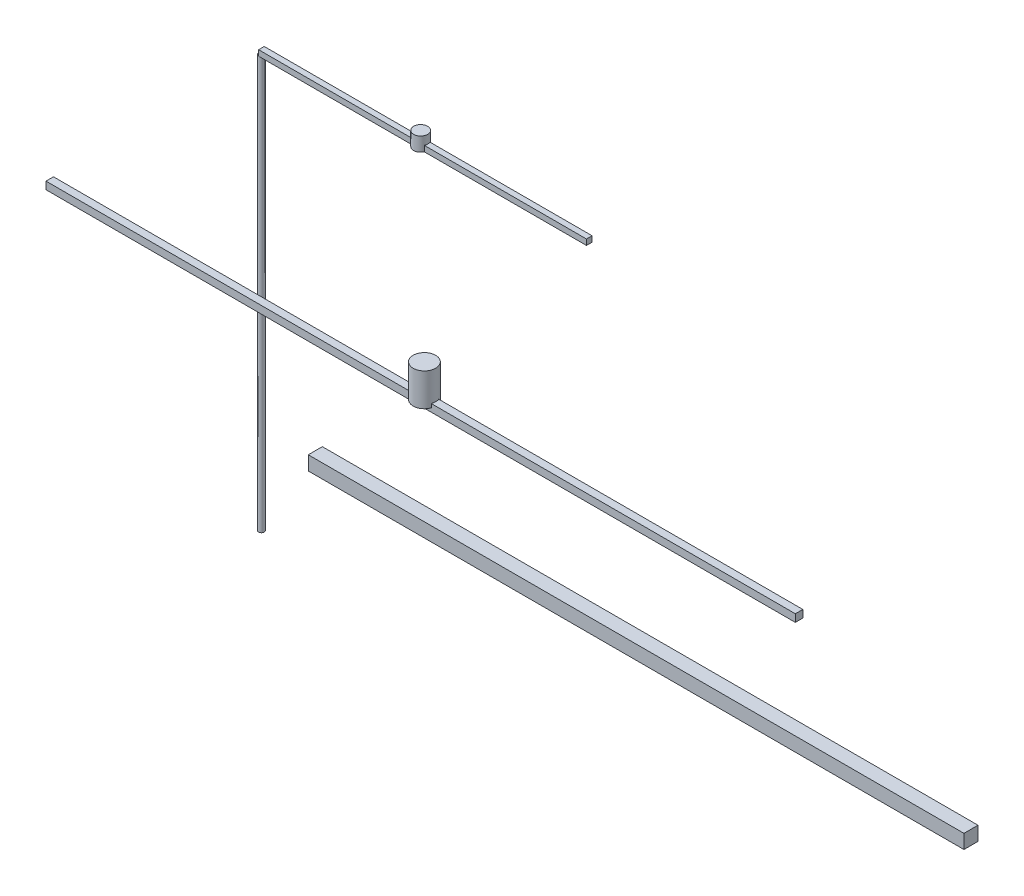
SolidWorks part; units mm, degrees
ref_plane "Front Plane" through (0, 0, 0) normal (0, 0, 1) x (1, 0, 0)
ref_plane "Top Plane" through (0, 0, 0) normal (0, 1, 0) x (1, 0, 0)
ref_plane "Right Plane" through (0, 0, 0) normal (1, 0, 0) x (0, 0, -1)
other "Configuration Table"
sketch "Sketch1" plane through (0, 0, 0) normal (0, 1, 0) x (1, 0, 0)
  circle A0 centre (-3500, 0) radius 30
extrude "Boss-Extrude1" add sketch "Sketch1" along normal blind 4400
sketch "Sketch2" plane through (0, 0, 0) normal (0, 1, 0) x (1, 0, 0)
  line L1 (-3500, -30) -> (0, -30)
  line L2 (-3500, -30) -> (-3500, 30)
  line L3 (-3500, 30) -> (0, 30)
  line L4 (0, -30) -> (0, 30)
  circle A0 centre (-3500, 0) radius 30 construction
extrude "Boss-Extrude2" add sketch "Sketch2" along normal blind 60 from offset 4400
sketch "Sketch3" plane through (0, 0, 0) normal (0, 1, 0) x (1, 0, 0)
  circle A0 centre (-1800, 0) radius 75
extrude "Boss-Extrude3" add sketch "Sketch3" along normal blind 150 from offset 4400
sketch "Sketch4" plane through (0, 0, 0) normal (0, 1, 0) x (1, 0, 0)
  line L1 (-4000, -1800) -> (4000, -1800)
  line L2 (-4000, -1800) -> (-4000, -1720)
  line L3 (-4000, -1720) -> (4000, -1720)
  line L4 (4000, -1800) -> (4000, -1720)
extrude "Boss-Extrude4" add sketch "Sketch4" along normal blind 80 from offset 3800
sketch "Sketch5" plane through (0, 0, 0) normal (0, 1, 0) x (1, 0, 0)
  circle A0 centre (0, -1760) radius 120
extrude "Boss-Extrude5" add sketch "Sketch5" along normal blind 350 from offset 3840
sketch "Sketch6" plane through (0, 0, 0) normal (0, 1, 0) x (1, 0, 0)
  line L1 (-3500, 500) -> (3500, 500)
  line L2 (-3500, 500) -> (-3500, 650)
  line L3 (-3500, 650) -> (3500, 650)
  line L4 (3500, 500) -> (3500, 650)
extrude "Boss-Extrude6" add sketch "Sketch6" along normal blind 150 from offset 300
